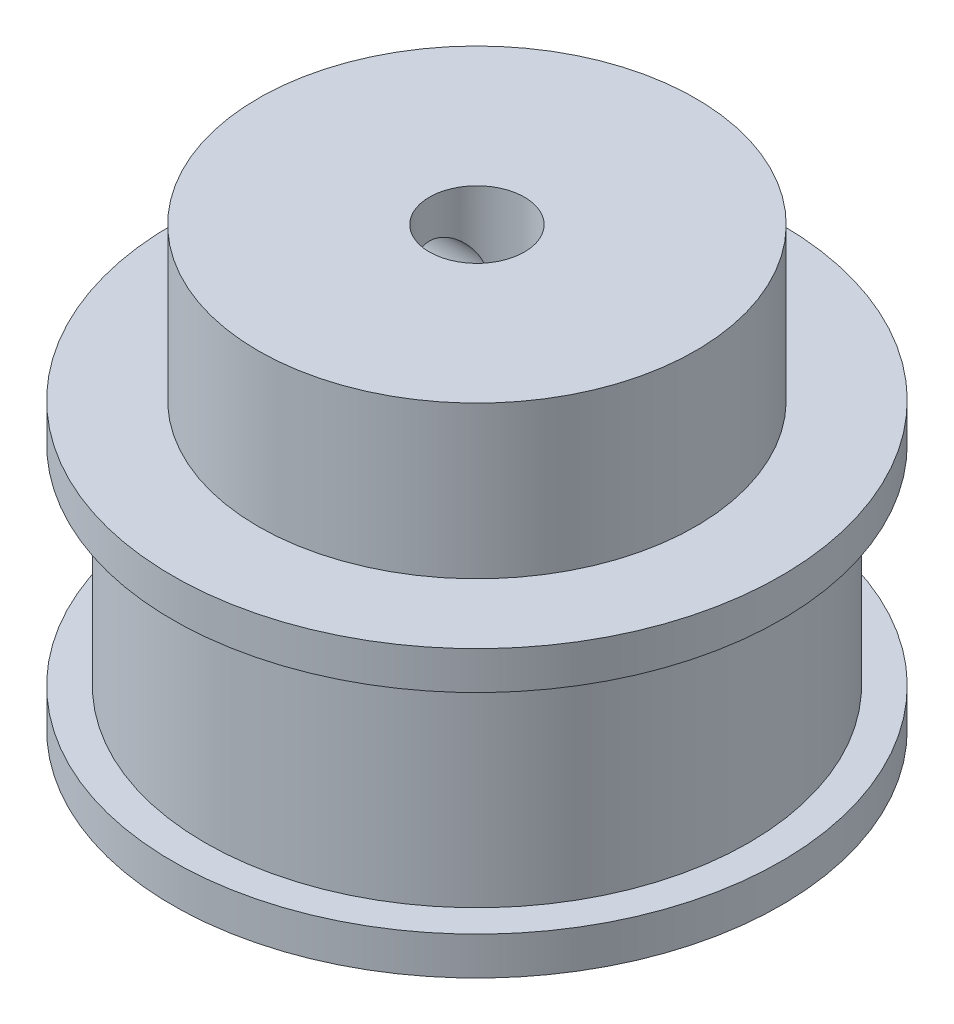
SolidWorks part; units mm, degrees
ref_plane "前视基准面" through (0, 0, 0) normal (0, 0, 1) x (1, 0, 0)
ref_plane "上视基准面" through (0, 0, 0) normal (0, 1, 0) x (1, 0, 0)
ref_plane "右视基准面" through (0, 0, 0) normal (1, 0, 0) x (0, 0, -1)
other "Configuration Table"
sketch "草图1" plane through (0, 0, 0) normal (0, 1, 0) x (1, 0, 0)
  circle A0 centre (0, 0) radius 11.5
  circle A1 centre (0, 0) radius 2.5
  dimension "D1" = 23
  dimension "D2" = 5
extrude "凸台-拉伸1" add sketch "草图1" along normal blind 8
sketch "草图2" plane through (0, 0, 0) normal (0, -1, 0) x (1, 0, 0)
  circle A0 centre (0, 0) radius 16
  dimension "D1" = 32
extrude "凸台-拉伸2" add sketch "草图2" along normal blind 2
sketch "草图3" plane through (0, -2, 0) normal (0, -1, 0) x (1, 0, 0)
  circle A0 centre (0, 0) radius 14.3
  dimension "D1" = 28.6
extrude "凸台-拉伸3" add sketch "草图3" along normal blind 11
sketch "草图4" plane through (0, -13, 0) normal (0, -1, 0) x (1, 0, 0)
  circle A0 centre (0, 0) radius 16 construction
  circle A1 centre (0, 0) radius 16
extrude "凸台-拉伸4" add sketch "草图4" along normal blind 2
sketch "草图5" plane through (0, 0, 0) normal (1, 0, 0) x (0, 0, -1)
  line L0 (0, 0) -> (0, 8) construction
  line L1 (2.5, 8) -> (-2.5, 8) construction
  circle A0 centre (0, 4) radius 2
  dimension "D1" = 4
extrude "切除-拉伸1" cut sketch "草图5" against normal blind 19
sketch "草图6" plane through (0, -15, 0) normal (0, -1, 0) x (1, 0, 0)
  circle A1 centre (0, 0) radius 16
  circle A2 centre (0, 0) radius 16
  point P0 (0, 0)
  dimension "D1" = 0
